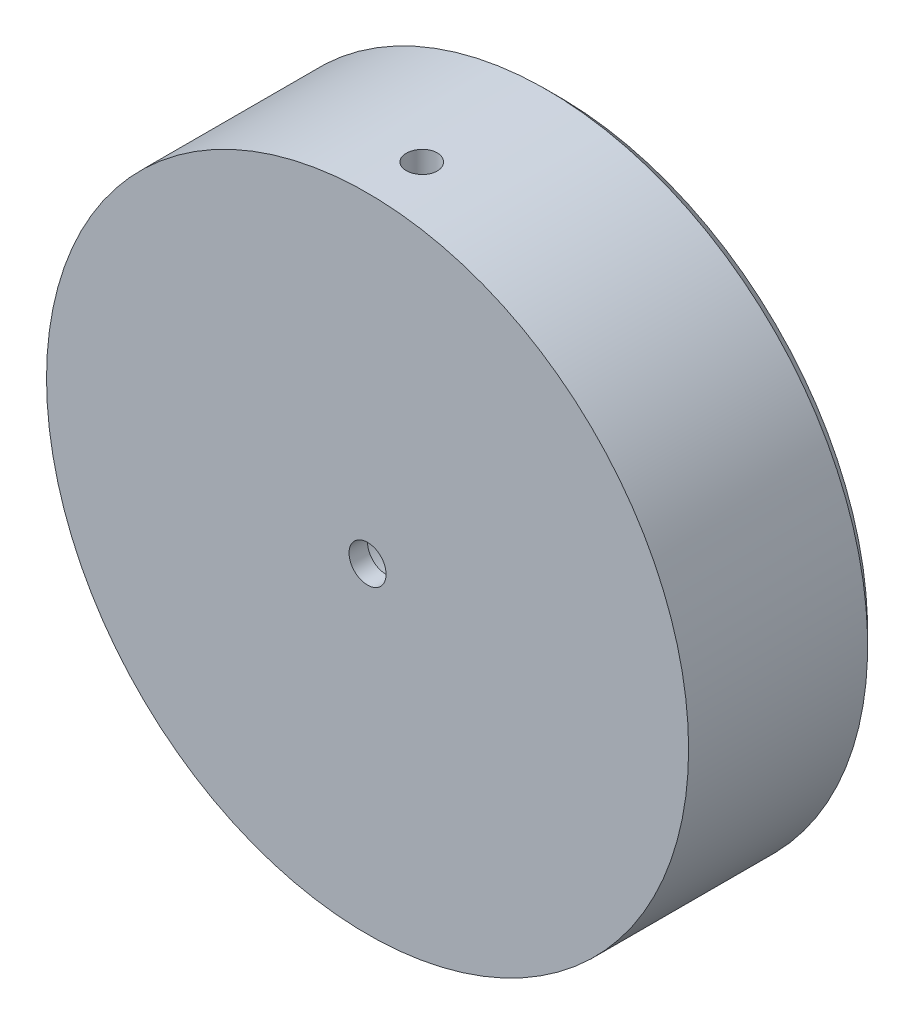
SolidWorks part; units mm, degrees
material "Náilon 6/10"
ref_plane "Plano frontal" through (0, 0, 0) normal (0, 0, 1) x (1, 0, 0)
ref_plane "Plano superior" through (0, 0, 0) normal (0, 1, 0) x (1, 0, 0)
ref_plane "Plano direito" through (0, 0, 0) normal (1, 0, 0) x (0, 0, -1)
sketch "Esboço1" plane through (0, 0, 0) normal (0, 0, 1) x (1, 0, 0)
  circle A0 centre (0, 0) radius 13.905
  circle A1 centre (0, 0) radius 26
extrude "Ressalto-extrusão1" add sketch "Esboço1" along normal blind 11
sketch "Esboço2" plane through (0, 0, 11) normal (0, 0, 1) x (1, 0, 0)
  circle A0 centre (0, 0) radius 26
extrude "Ressalto-extrusão2" add sketch "Esboço2" along normal blind 6.5
sketch "Esboço3" plane through (0, 0, 17.5) normal (0, 0, 1) x (1, 0, 0)
  circle A0 centre (0, 0) radius 1.5
extrude "Corte-extrusão1" cut sketch "Esboço3" against normal blind 40
sketch "Esboço4" plane through (0, 0, 11) normal (0, 0, -1) x (-1, 0, 0)
  circle A0 centre (0, 0) radius 4.5
extrude "Corte-extrusão2" cut sketch "Esboço4" against normal blind 5
sketch "Esboço5" plane through (0, 0, 17.5) normal (0, 0, 1) x (1, 0, 0)
  line L0 (0, 26) -> (0, -26) construction
  line L1 (-26, 0) -> (26, 0) construction
  line L2 (-2, 11.619) -> (-2, 7)
  line L4 (-11.619, 2) -> (-7, 2)
  line L5 (2, 11.619) -> (2, 7)
  line L6 (7, 2) -> (11.619, 2)
  line L8 (-26, 2) -> (26, 2) construction
  line L9 (2, -7) -> (2, -11.619)
  line L10 (-2, 26) -> (-2, -26) construction
  line L11 (7, -2) -> (11.619, -2)
  line L12 (2, 26) -> (2, -26) construction
  line L23 (-2, -7) -> (-2, -11.619)
  line L24 (-7, -2) -> (-11.619, -2)
  circle A0 centre (0, 0) radius 26 construction
  arc A1 (-2, 7) -> (-7, 2) centre (-7, 7) cw
  arc A22 (2, 7) -> (7, 2) centre (7, 7) ccw
  arc A23 (7, -2) -> (2, -7) centre (7, -7) ccw
  arc A27 (-3.25, 12.5872) -> (-12.5872, 3.25) centre (0, 0) ccw
  arc A28 (-3.25, -12.5872) -> (-2, -11.619) centre (-3, -11.619) ccw
  arc A30 (12.5872, 3.25) -> (3.25, 12.5872) centre (0, 0) ccw
  arc A31 (3.25, -12.5872) -> (12.5872, -3.25) centre (0, 0) ccw
  arc A32 (-12.5872, 3.25) -> (-11.619, 2) centre (-11.619, 3) ccw
  arc A33 (-3.25, 12.5872) -> (-2, 11.619) centre (-3, 11.619) cw
  arc A34 (3.25, 12.5872) -> (2, 11.619) centre (3, 11.619) ccw
  arc A35 (12.5872, 3.25) -> (11.619, 2) centre (11.619, 3) cw
  arc A36 (12.5872, -3.25) -> (11.619, -2) centre (11.619, -3) ccw
  arc A37 (3.25, -12.5872) -> (2, -11.619) centre (3, -11.619) cw
  arc A40 (-7, -2) -> (-2, -7) centre (-7, -7) cw
  arc A41 (-12.5872, -3.25) -> (-11.619, -2) centre (-11.619, -3) cw
  arc A42 (-3.25, -12.5872) -> (-12.5872, -3.25) centre (0, 0) cw
  point P9 (-20, -2)
  point P10 (20, -2)
  point P37 (2, -12.8452)
  point P41 (-2, 17.8885)
  point P44 (2, 17.8885)
  point P47 (17.8885, 2)
  point P50 (17.8885, -2)
  point P53 (2, -17.8885)
  dimension "D5" = 1
  dimension "D3" = 5
  dimension "D1" = 2
  dimension "D2" = 2
sketch "Esboço6" plane through (0, 0, 0) normal (0, 0, -1) x (-1, 0, 0)
  circle A0 centre (0, 0) radius 41
extrude "Corte-extrusão4" cut sketch "Esboço6" against normal blind 2
chamfer "Chanfro1" distance 1 angle 45 1 edges at (-26, 0, 2)
sketch "Esboço7" plane through (0, 0, 0) normal (0, 1, 0) x (1, 0, 0)
  line L0 (0, -0.7808) -> (0, -17.5) construction
  line L1 (-26, -17.5) -> (26, -17.5) construction
  line L2 (0, -10.9046) -> (0, -13.1146) construction
  line L3 (0, -16.0146) -> (2.6267, -16.0146) construction
  circle A0 centre (0, -13.1146) radius 1.25
  dimension "D1" = 2.9
extrude "Corte-extrusão5" cut sketch "Esboço7" against normal blind 61 and the other way blind 52
